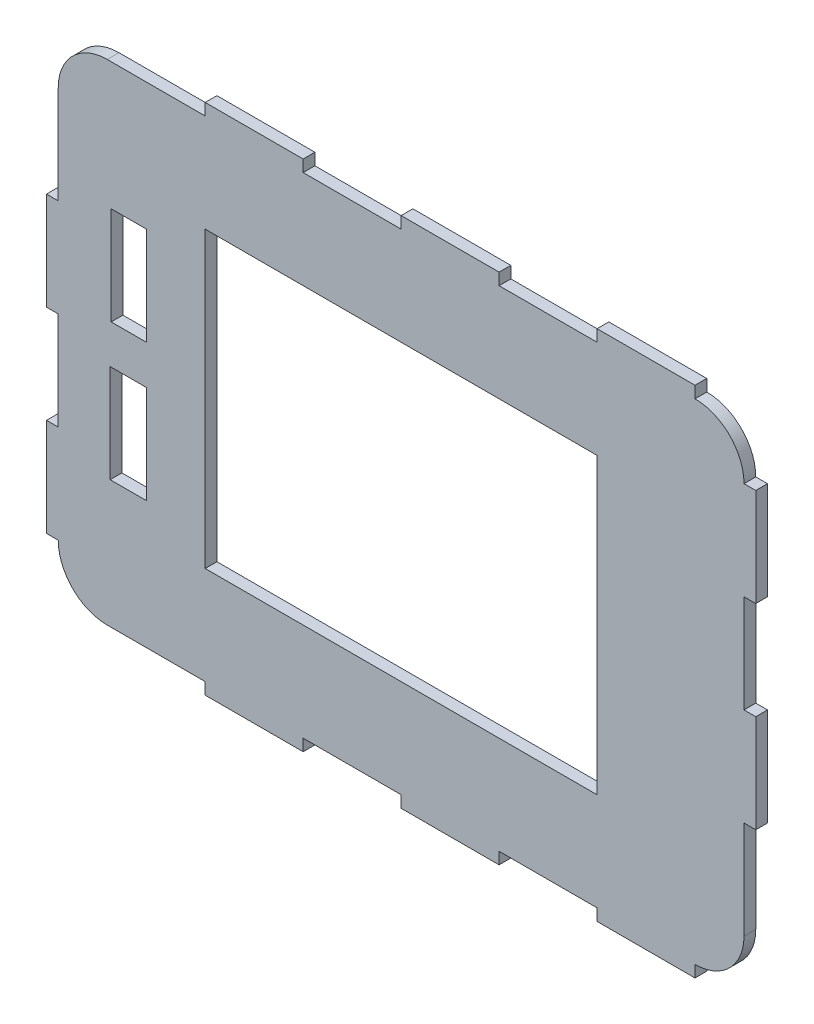
SolidWorks part; units mm, degrees
material "Perspex (TM) Plaque acrylique coulée"
ref_plane "Plan de face" through (0, 0, 0) normal (0, 0, 1) x (1, 0, 0)
ref_plane "Plan de dessus" through (0, 0, 0) normal (0, 1, 0) x (1, 0, 0)
ref_plane "Plan de droite" through (0, 0, 0) normal (1, 0, 0) x (0, 0, -1)
sketch "Esquisse1" plane through (0, 0, 0) normal (0, 0, 1) x (1, 0, 0)
  line L46 (0, 0) -> (0, 6)
  line L47 (0, 6) -> (50, 6)
  line L48 (50, 6) -> (50, 0)
  line L49 (50, 0) -> (100, 0)
  line L50 (100, 0) -> (100, 6)
  line L51 (100, 6) -> (150, 6)
  line L52 (150, 6) -> (150, 0)
  line L53 (150, 0) -> (200, 0)
  line L54 (200, 0) -> (200, 6)
  line L55 (200, 6) -> (250, 6)
  line L56 (250, 6) -> (250, 0)
  line L57 (0, 0) -> (-50, 0)
  line L58 (275, -25) -> (281, -25)
  line L59 (281, -25) -> (281, -75)
  line L60 (281, -75) -> (275, -75)
  line L61 (275, -75) -> (275, -125)
  line L62 (275, -125) -> (281, -125)
  line L63 (281, -125) -> (281, -175)
  line L64 (281, -175) -> (275, -175)
  line L65 (275, -175) -> (275, -225)
  line L66 (250, -250) -> (250, -256)
  line L67 (250, -256) -> (200, -256)
  line L68 (200, -256) -> (200, -250)
  line L69 (200, -250) -> (150, -250)
  line L70 (150, -250) -> (150, -256)
  line L71 (150, -256) -> (100, -256)
  line L72 (100, -256) -> (100, -250)
  line L73 (100, -250) -> (50, -250)
  line L74 (50, -250) -> (50, -256)
  line L75 (50, -256) -> (0, -256)
  line L76 (0, -256) -> (0, -250)
  line L77 (0, -250) -> (-50, -250)
  line L78 (-75, -225) -> (-81, -225)
  line L79 (-81, -225) -> (-81, -175)
  line L80 (-81, -175) -> (-75, -175)
  line L81 (-75, -175) -> (-75, -125)
  line L82 (-75, -125) -> (-81, -125)
  line L83 (-81, -125) -> (-81, -75)
  line L84 (-81, -75) -> (-75, -75)
  line L85 (-75, -75) -> (-75, -25)
  line L87 (0, -50) -> (200, -50)
  line L88 (0, -50) -> (0, -200)
  line L89 (0, -200) -> (200, -200)
  line L90 (200, -50) -> (200, -200)
  line L91 (-48, -65) -> (-30, -65)
  line L92 (-48, -65) -> (-48, -115)
  line L93 (-48, -115) -> (-30, -115)
  line L94 (-30, -65) -> (-30, -115)
  line L95 (-30, -135) -> (-48.5078, -135)
  line L96 (-30, -135) -> (-30, -185)
  line L97 (-30, -185) -> (-48.5078, -185)
  line L98 (-48.5078, -135) -> (-48.5078, -185)
  arc A4 (250, 0) -> (275, -25) centre (250, -25) cw
  arc A5 (275, -225) -> (250, -250) centre (250, -225) cw
  arc A6 (-50, -250) -> (-75, -225) centre (-50, -225) cw
  arc A7 (-50, 0) -> (-75, -25) centre (-50, -25) ccw
  dimension "D10" = 25
  dimension "D20" = 25
  dimension "D33" = 25
  dimension "D1" = 50
  dimension "D2" = 50
  dimension "D3" = 50
  dimension "D4" = 50
  dimension "D5" = 50
  dimension "D6" = 50
  dimension "D7" = 6
  dimension "D8" = 6
  dimension "D9" = 6
  dimension "D11" = 6
  dimension "D12" = 50
  dimension "D13" = 6
  dimension "D14" = 50
  dimension "D15" = 6
  dimension "D16" = 50
  dimension "D17" = 50
  dimension "D18" = 6
  dimension "D19" = 6
  dimension "D21" = 6
  dimension "D22" = 50
  dimension "D23" = 6
  dimension "D24" = 50
  dimension "D25" = 6
  dimension "D26" = 50
  dimension "D27" = 6
  dimension "D28" = 50
  dimension "D29" = 6
  dimension "D30" = 50
  dimension "D31" = 6
  dimension "D32" = 50
  dimension "D34" = 6
  dimension "D35" = 6
  dimension "D36" = 6
  dimension "D37" = 6
  dimension "D38" = 50
  dimension "D39" = 50
  dimension "D40" = 50
  dimension "D41" = 50
  dimension "D42" = 150
  dimension "D43" = 200
  dimension "D44" = 50
  dimension "D45" = 75
  dimension "D46" = 50
  dimension "D47" = 18
  dimension "D48" = 18.5078
  dimension "D49" = 50
  dimension "D50" = 65
  dimension "D51" = 20
  dimension "D52" = 30
  dimension "D53" = 30
extrude "Boss.-Extru.1" add sketch "Esquisse1" along normal blind 6
